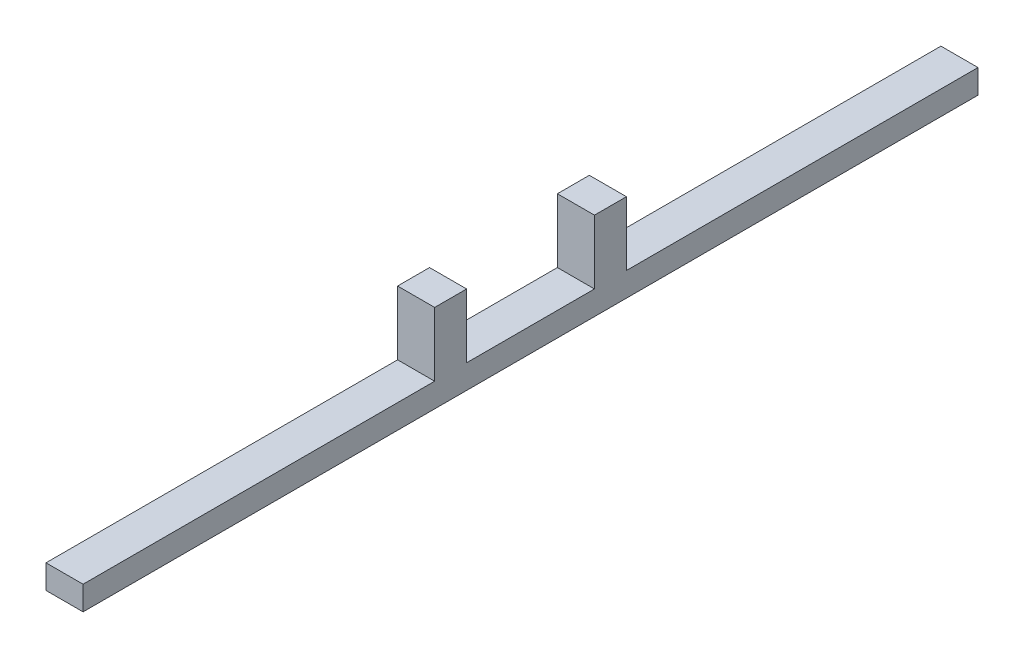
SolidWorks part; units mm, degrees
material "Choose your Material"
ref_plane "Front Plane" through (0, 0, 0) normal (0, 0, 1) x (1, 0, 0)
ref_plane "Top Plane" through (0, 0, 0) normal (0, 1, 0) x (1, 0, 0)
ref_plane "Right Plane" through (0, 0, 0) normal (1, 0, 0) x (0, 0, -1)
sketch "Sketch1" plane through (0, 0, 0) normal (0, 0, 1) x (1, 0, 0)
  line L0 (-14.732, 0) -> (14.732, 0)
  line L1 (14.732, 0) -> (14.732, -19.05)
  line L3 (-14.732, -19.05) -> (-14.732, 0)
  line L4 (-14.732, -19.05) -> (14.732, -19.05)
  point P4 (0, 0)
  dimension "D1" = 19.05
  dimension "D2" = 29.464
extrude "Boss-Extrude1" add sketch "Sketch1" along normal mid plane 711.2
sketch "Sketch2" plane through (0, 0, 0) normal (0, 1, 0) x (1, 0, 0)
  line L0 (-14.732, -355.6) -> (-14.732, 355.6) construction
  line L1 (-14.732, 76.2) -> (14.732, 76.2)
  line L2 (-14.732, 76.2) -> (-14.732, 50.8)
  line L3 (-14.732, 50.8) -> (14.732, 50.8)
  line L4 (14.732, 76.2) -> (14.732, 50.8)
  line L5 (14.732, -355.6) -> (14.732, 355.6) construction
  line L6 (0, -50.8) -> (0, 50.8) construction
  line L7 (-14.732, -50.8) -> (14.732, -50.8)
  line L8 (-14.732, -50.8) -> (-14.732, -76.2)
  line L9 (-14.732, -76.2) -> (14.732, -76.2)
  line L10 (14.732, -50.8) -> (14.732, -76.2)
  point P16 (0, 0)
  dimension "D1" = 25.4
  dimension "D2" = 25.4
  dimension "D3" = 101.6
extrude "Boss-Extrude2" add sketch "Sketch2" along normal blind 50.8
sketch "Sketch3" plane through (14.732, 0, 0) normal (1, 0, 0) x (0, 0, -1)
  line L0 (-50.8, 0) -> (50.8, 0) construction
  line L1 (-25.4, 0) -> (25.4, 0)
  line L2 (-25.4, 0) -> (-25.4, -19.05)
  line L3 (-25.4, -19.05) -> (25.4, -19.05)
  line L4 (25.4, 0) -> (25.4, -19.05)
  line L5 (-355.6, -19.05) -> (355.6, -19.05) construction
  point P8 (0, 0)
  dimension "D1" = 50.8
